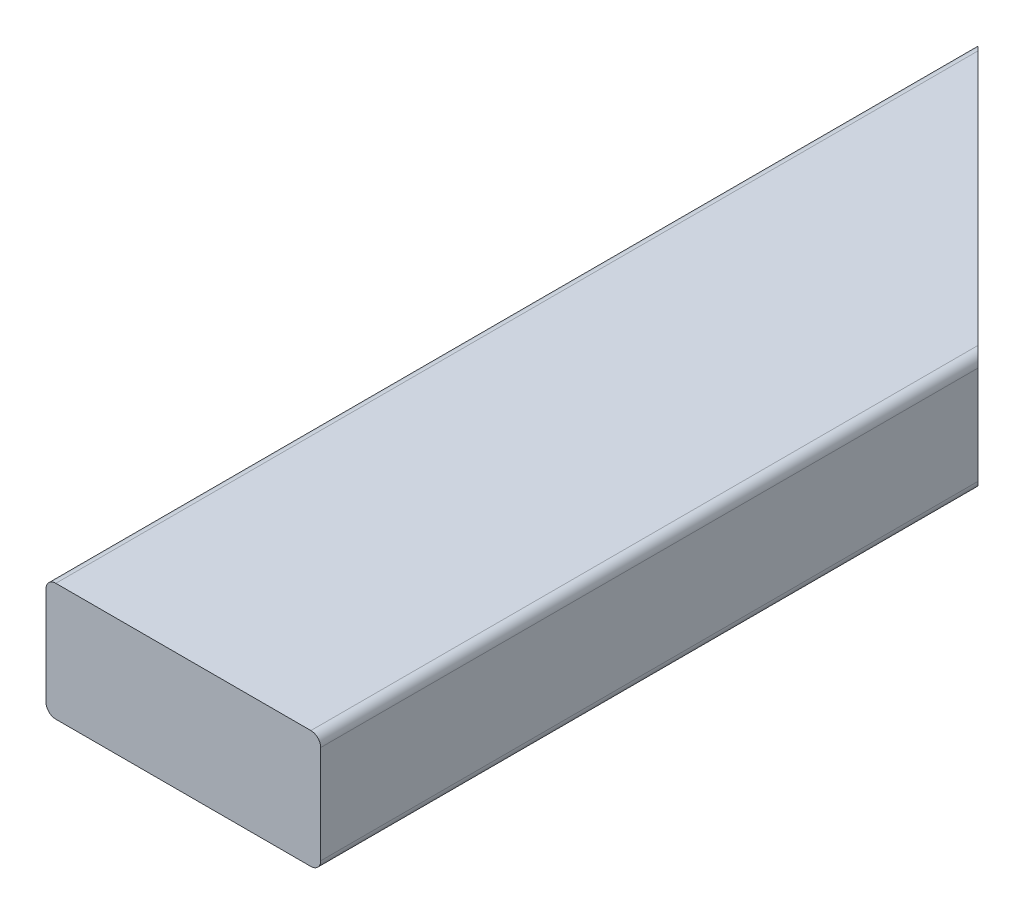
SolidWorks part; units mm, degrees
material "Pine"
ref_plane "Front Plane" through (0, 0, 0) normal (0, 0, 1) x (1, 0, 0)
ref_plane "Top Plane" through (0, 0, 0) normal (0, 1, 0) x (1, 0, 0)
ref_plane "Right Plane" through (0, 0, 0) normal (1, 0, 0) x (0, 0, -1)
sketch "Sketch1" plane through (0, 0, 0) normal (0, 1, 0) x (1, 0, 0)
  line L0 (0, 0) -> (-88.9, 88.9)
  line L1 (-88.9, 88.9) -> (-88.9, -212.725)
  line L2 (-88.9, -212.725) -> (0, -212.725)
  line L3 (0, -212.725) -> (0, 0)
  dimension "D1" = 88.9
  dimension "D2" = 45
  dimension "D3" = 212.725
  dimension "D4" = 301.625
extrude "Boss-Extrude1" add sketch "Sketch1" along normal blind 38.1
fillet "Fillet1" radius 3.175 4 edges at (-88.9, 0, 61.9125) (-88.9, 38.1, 61.9125) (0, 0, 106.3625) (0, 38.1, 106.3625)
